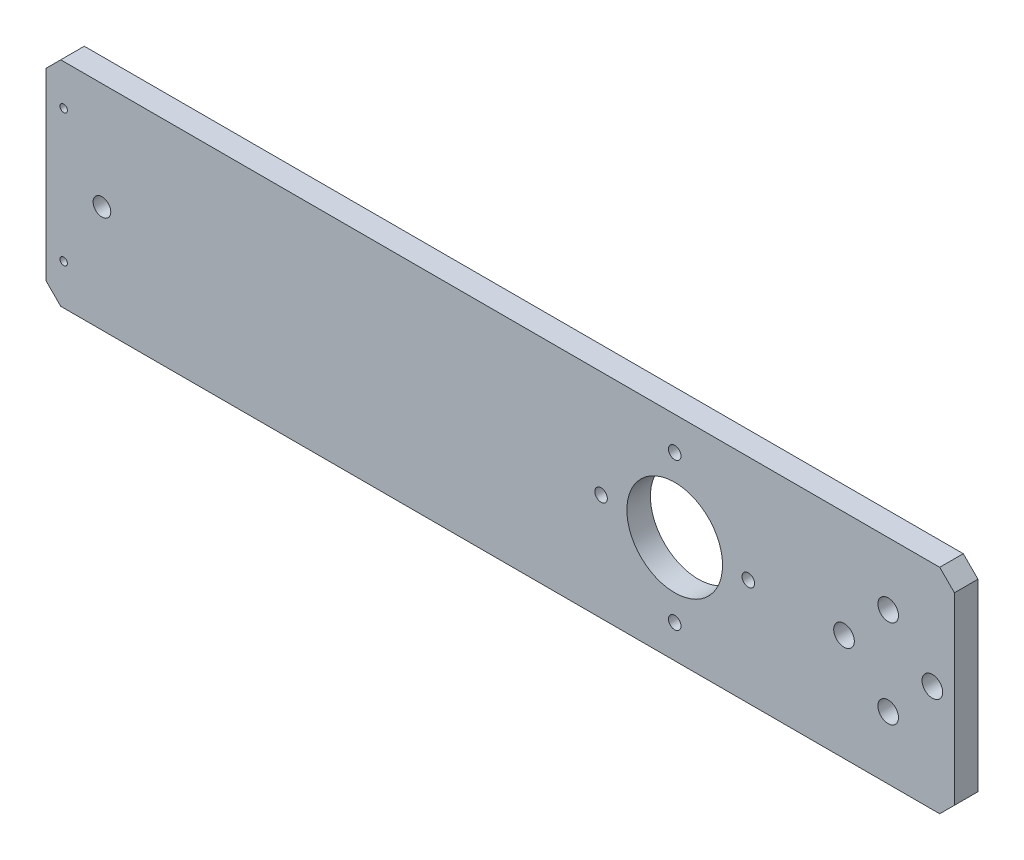
SolidWorks part; units mm, degrees
ref_plane "前视基准面" through (0, 0, 0) normal (0, 0, 1) x (1, 0, 0)
ref_plane "上视基准面" through (0, 0, 0) normal (0, 1, 0) x (1, 0, 0)
ref_plane "右视基准面" through (0, 0, 0) normal (1, 0, 0) x (0, 0, -1)
sketch "草图1" plane through (0, 0, 0) normal (0, 0, 1) x (1, 0, 0)
  line L0 (637.6876, 879.678) -> (637.6876, 754.678)
  line L3 (647.6876, 744.678) -> (1244.6876, 744.678)
  line L6 (1244.6876, 889.678) -> (647.6876, 889.678)
  line L7 (1244.6876, 744.678) -> (1254.6876, 754.678)
  line L8 (1254.6876, 879.678) -> (1244.6876, 889.678)
  line L9 (1254.6876, 754.678) -> (1254.6876, 879.678)
  line L10 (647.6876, 889.678) -> (637.6876, 879.678)
  line L11 (637.6876, 754.678) -> (647.6876, 744.678)
  circle A3 centre (1209.6876, 787.178) radius 7
  circle A4 centre (1064.6876, 767.178) radius 3
  circle A6 centre (1064.6876, 817.178) radius 32.5
  circle A7 centre (1014.6876, 817.178) radius 3
  circle A8 centre (1114.6876, 817.178) radius 3
  circle A9 centre (1064.6876, 867.178) radius 3
  circle A10 centre (1239.6876, 817.178) radius 7
  circle A11 centre (1179.6876, 817.178) radius 7
  circle A12 centre (1209.6876, 847.178) radius 7
  point P2 (637.6876, 889.678)
  point P17 (637.6876, 744.678)
  dimension "D5" = 6
  dimension "D6" = 190
  dimension "D1" = 10
  dimension "D2" = 45
  dimension "D3" = 10
  dimension "D4" = 45
  dimension "D7" = 140
  dimension "D8" = 190
  dimension "D9" = 190
  dimension "D10" = 240
extrude "凸台-拉伸1" add sketch "草图1" along normal blind 16
hole_wizard "M14 螺纹孔1" positions "草图3" profile "草图2" tap size "M14" standard "GB"
sketch "草图3" plane through (0, 0, 16) normal (0, 0, 1) x (1, 0, 0)
  line L0 (637.6876, 879.678) -> (637.6876, 754.678) construction
  point P1 (675.6876, 817.178)
  dimension "D1" = 38
sketch "草图2" plane through (675.6876, 817.178, 16) normal (1, 0, 0) x (0, -1, 0)
  line L0 (0, 0) -> (0, 37.6052)
  line L1 (0, 37.6052) -> (6, 34)
  line L2 (6, 34) -> (6, 0)
  line L5 (6, 0) -> (0, 0)
  line L10 (0, 37.6052) -> (-6, 34) construction
  line L11 (0, -6.35) -> (0, 107.95) construction
  dimension "螺纹孔钻头直径" = 12
  dimension "螺纹孔钻头深度" = 34
  dimension "导头角度" = 118
cosmetic thread "孔螺蚊线1" parameters "D1"=16, "D2"=14
hole_wizard "M6 螺纹孔1" positions "草图5" profile "草图4" tap size "M6" standard "ISO"
sketch "草图5" plane through (0, 0, 0) normal (0, 0, -1) x (-1, 0, 0)
  line L0 (-654.6876, 772.178) -> (-644.6876, 772.178) construction
  line L2 (-654.6876, 862.178) -> (-644.6876, 862.178) construction
  point P10 (-649.6876, 772.178)
  point P12 (-649.6876, 862.178)
sketch "草图4" plane through (649.6876, 772.178, 0) normal (1, 0, 0) x (0, 1, 0)
  line L0 (0, 0) -> (0, 19.5022)
  line L1 (0, 19.5022) -> (2.5, 18)
  line L2 (2.5, 18) -> (2.5, 0)
  line L5 (2.5, 0) -> (0, 0)
  line L10 (0, 19.5022) -> (-2.5, 18) construction
  line L11 (0, -6.35) -> (0, 107.95) construction
  dimension "螺纹孔钻头直径" = 5
  dimension "螺纹孔钻头深度" = 18
  dimension "导头角度" = 118
cosmetic thread "孔螺蚊线2" parameters "D1"=15, "D2"=6
cosmetic thread "孔螺蚊线3" parameters "D1"=15, "D2"=6
hole_wizard "M10 螺纹孔2" positions "草图9" profile "草图8" tap size "M10" standard "GB"
sketch "草图9" plane through (0, 0, 16) normal (0, 0, 1) x (1, 0, 0)
  point P1 (1014.6876, 817.178)
  point P5 (1064.6876, 767.178)
  point P8 (1114.6876, 817.178)
  point P11 (1064.6876, 867.178)
sketch "草图8" plane through (1014.6876, 817.178, 16) normal (1, 0, 0) x (0, -1, 0)
  line L0 (0, 0) -> (0, 27.0537)
  line L1 (0, 27.0537) -> (4.25, 24.5)
  line L2 (4.25, 24.5) -> (4.25, 0)
  line L5 (4.25, 0) -> (0, 0)
  line L10 (0, 27.0537) -> (-4.25, 24.5) construction
  line L11 (0, -6.35) -> (0, 107.95) construction
  dimension "螺纹孔钻头直径" = 8.5
  dimension "螺纹孔钻头深度" = 24.5
  dimension "导头角度" = 118
cosmetic thread "孔螺蚊线6" parameters "D1"=16, "D2"=10
cosmetic thread "孔螺蚊线7" parameters "D1"=16, "D2"=10
cosmetic thread "孔螺蚊线8" parameters "D1"=16, "D2"=10
cosmetic thread "孔螺蚊线9" parameters "D1"=16, "D2"=10
